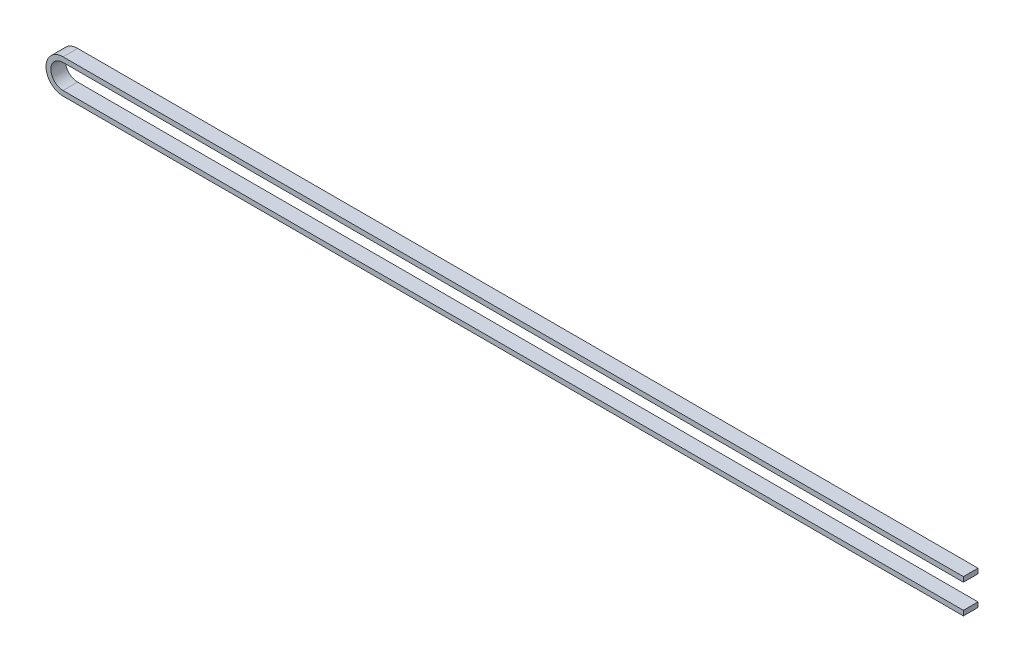
SolidWorks part; units mm, degrees
ref_plane "Спереди" through (0, 0, 0) normal (0, 0, 1) x (1, 0, 0)
ref_plane "Сверху" through (0, 0, 0) normal (0, 1, 0) x (1, 0, 0)
ref_plane "Справа" through (0, 0, 0) normal (1, 0, 0) x (0, 0, -1)
sketch "Эскиз1" plane through (0, 0, 0) normal (0, 1, 0) x (1, 0, 0)
  line L1 (0, 0) -> (370, 0)
  line L2 (0, 0) -> (0, 6)
  line L3 (0, 6) -> (370, 6)
  line L4 (370, 0) -> (370, 6)
  dimension "D1" = 6
  dimension "D2" = 370
extrude "Бобышка-Вытянуть1" add sketch "Эскиз1" along normal blind 2
sketch "Эскиз2" plane through (0, 0, 0) normal (0, 0, 1) x (1, 0, 0)
  line L0 (0, 2) -> (0, 0) construction
  line L1 (0, 12) -> (370, 12)
  line L2 (0, 12) -> (0, 14)
  line L3 (0, 14) -> (370, 14)
  line L4 (370, 12) -> (370, 14)
  line L5 (370, 2) -> (370, 0) construction
  line L6 (0, 2) -> (370, 2) construction
  line L7 (0, 12) -> (0, 2) construction
  arc A0 (0, 0) -> (0, 14) centre (0, 7) cw
  arc A1 (0, 2) -> (0, 12) centre (0, 7) cw
  line M7 (0, 2) -> (0, 0)
  dimension "D1" = 2
  dimension "D2" = 10
extrude "Бобышка-Вытянуть2" add sketch "Эскиз2" against normal blind 6 contours A1 L2 A0 M7 | L1 L4 L3 L2
